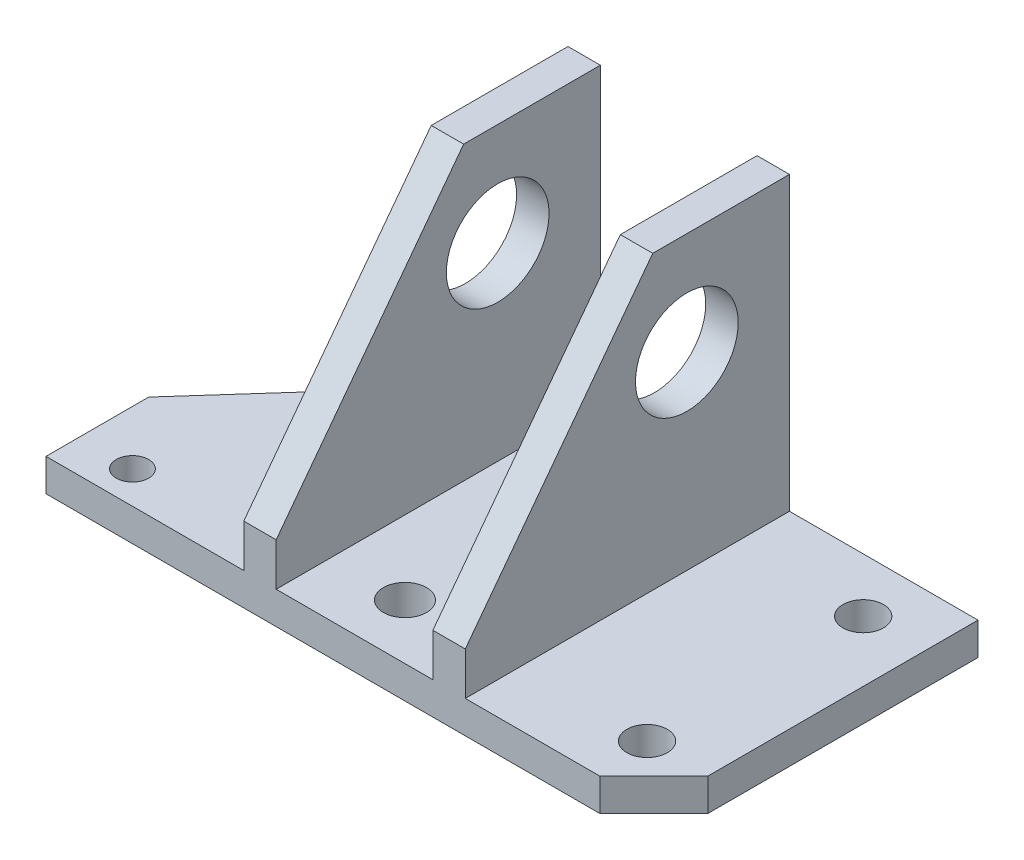
SolidWorks part; units mm, degrees
ref_plane "Front Plane" through (0, 0, 0) normal (0, 0, 1) x (1, 0, 0)
ref_plane "Top Plane" through (0, 0, 0) normal (0, 1, 0) x (1, 0, 0)
ref_plane "Right Plane" through (0, 0, 0) normal (1, 0, 0) x (0, 0, -1)
sketch "Sketch1" plane through (0, 0, 0) normal (0, 0, 1) x (1, 0, 0)
  line L0 (-88.4843, 0) -> (119.3926, 0) construction
  line L1 (0, 103.5692) -> (0, -92.4923) construction
  line L2 (-112.5, 0) -> (-112.5, -12)
  line L3 (-112.5, -12) -> (112.5, -12)
  line L4 (112.5, -12) -> (112.5, 0)
  line L5 (112.5, 0) -> (42.712, 0)
  line L6 (42.712, 0) -> (42.712, 108)
  line L7 (42.712, 108) -> (30.712, 108)
  line L8 (30.712, 108) -> (30.712, 0)
  line L9 (30.712, 0) -> (-27.288, 0)
  line L10 (-27.288, 0) -> (-27.288, 108)
  line L11 (-27.288, 108) -> (-39.288, 108)
  line L12 (-39.288, 108) -> (-39.288, 0)
  line L13 (-39.288, 0) -> (-112.5, 0)
  dimension "D1" = 12
  dimension "D2" = 108
  dimension "D3" = 225
  dimension "D4" = 58
  dimension "D5" = 12
  dimension "D6" = 12
extrude "Boss-Extrude1" add sketch "Sketch1" along normal mid plane 120
sketch "Sketch2" plane through (0, 0, 0) normal (0, 1, 0) x (1, 0, 0)
  line L1 (-112.5, -60) -> (92.5, -60)
  line L2 (112.5, -60) -> (42.712, -60) construction
  line L3 (92.5, -60) -> (112.5, -60)
  line L4 (112.5, -60) -> (112.5, -40.0044)
  line L5 (112.5, -60) -> (112.5, 60) construction
  line L6 (112.5, -40.0044) -> (92.5, -60)
  dimension "D1" = 205
extrude "Cut-Extrude1" cut sketch "Sketch2" against normal blind 120 contours L4 L6 L3
sketch "Sketch3" plane through (0, 0, 0) normal (0, 1, 0) x (1, 0, 0)
  line L0 (92.5, -60) -> (42.712, -60) construction
  line L1 (-112.5, -60) -> (-112.5, -21.9974)
  line L3 (-114.6783, 0) -> (167.9326, 0) construction
  line L4 (0, 63.6219) -> (0, -100.7069) construction
  line L5 (-112.5, -60) -> (-112.5, 60) construction
  line L6 (-39.288, -60) -> (-112.5, -60) construction
  line L7 (-112.5, -21.9974) -> (-39.288, 60)
  line L8 (-39.288, 60) -> (-112.5, 60)
  line L9 (-112.5, 60) -> (-112.5, -21.9974)
  circle A0 centre (90, -40) radius 6
  circle A1 centre (-92.5, -48) radius 6
  circle A2 centre (0, -40) radius 8
  circle A3 centre (90, 40) radius 6
  circle A4 centre (0, 40) radius 8
  dimension "D1" = 12
  dimension "D4" = 12
  dimension "D5" = 16
  dimension "D2" = 20
  dimension "D3" = 90
  dimension "D6" = 20
  dimension "D7" = 12
extrude "Cut-Extrude2" cut sketch "Sketch3" against normal blind 120 contours L8 L9 L7
sketch "Sketch5" plane through (0, 0, 0) normal (1, 0, 0) x (0, 0, -1)
  line L0 (9.3889, 108) -> (-60, 108)
  line L1 (-60, 108) -> (-60, 15.8551)
  line L4 (-60, 108) -> (60, 108) construction
  line L5 (9.3889, 108) -> (-60, 15.8551)
  line L6 (-60, 0) -> (-60, 108) construction
extrude "Cut-Extrude3" cut sketch "Sketch5" against normal mid plane 120
sketch "Sketch7" plane through (0, 0, 0) normal (1, 0, 0) x (0, 0, -1)
  line L0 (60, 0) -> (60, 108) construction
  line L1 (9.3889, 108) -> (60, 108) construction
  circle A0 centre (22, 70) radius 19
  dimension "D1" = 38
  dimension "D2" = 38
  dimension "D3" = 38
extrude "Cut-Extrude4" cut sketch "Sketch7" against normal mid plane 120
sketch "Sketch8" plane through (0, 0, 0) normal (0, 1, 0) x (1, 0, 0)
  circle A0 centre (93.5815, 39.6259) radius 10.6451
  circle A1 centre (0, 39.6259) radius 9.1362
  circle A2 centre (-91.242, -48.1067) radius 6
  point P6 (0, 0)
  dimension "D1" = 12
sketch "Sketch10" plane through (0, 0, 0) normal (0, 1, 0) x (1, 0, 0)
  line L0 (-124.5804, 0) -> (162.8903, 0) construction
  line L1 (92.5, -60) -> (42.712, -60) construction
  line L3 (-112.5, -60) -> (-112.5, -21.9974) construction
  line L4 (-39.288, -60) -> (-112.5, -60) construction
  circle A0 centre (0, 39.6259) radius 8
  circle A1 centre (90, -40) radius 7.5075
  circle A2 centre (-92.5, -48) radius 6
  circle A3 centre (0, -39.6259) radius 8
  circle A4 centre (90, 40) radius 7.5075
  dimension "D1" = 12
  dimension "D2" = 16
  dimension "D3" = 20
  dimension "D5" = 20
  dimension "D4" = 90
  dimension "D6" = 12
extrude "Cut-Extrude5" cut sketch "Sketch10" against normal blind 120
sketch "Sketch13" plane through (-51.6691, 0, -46.1332) normal (-0.7459, 0, -0.666) x (-0.666, 0, 0.7459)
  line L0 (91.3355, -12) -> (91.3355, 12.0989)
